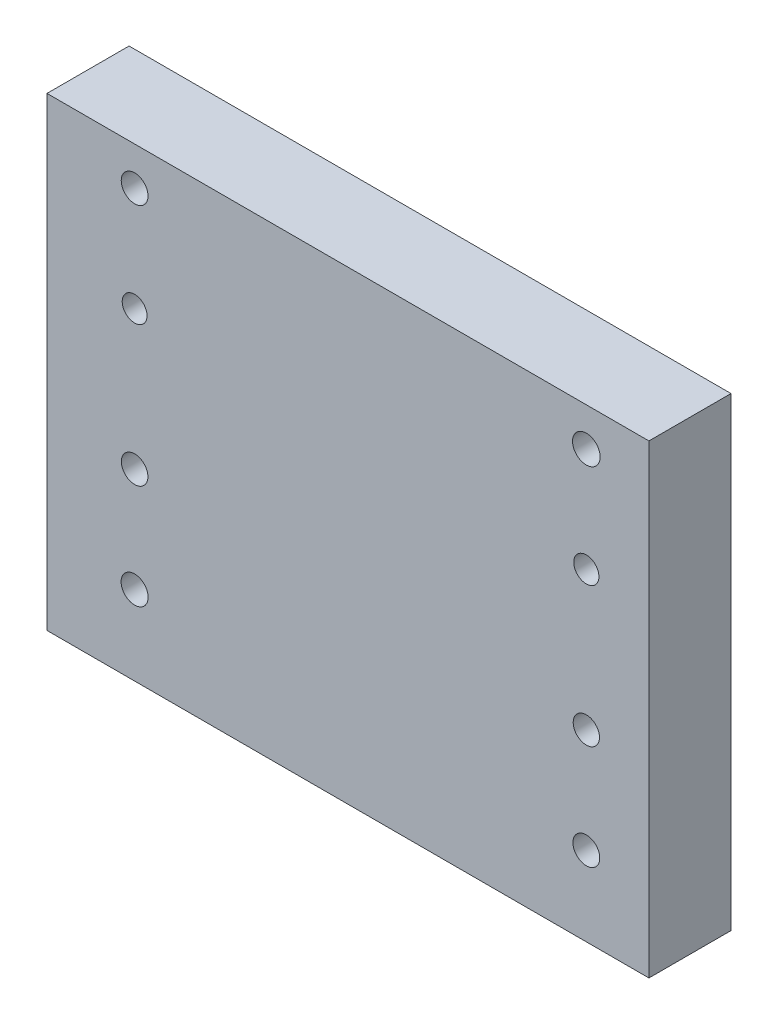
SolidWorks part; units mm, degrees
ref_plane "Plan de face" through (0, 0, 0) normal (0, 0, 1) x (1, 0, 0)
ref_plane "Plan de dessus" through (0, 0, 0) normal (0, 1, 0) x (1, 0, 0)
ref_plane "Plan de droite" through (0, 0, 0) normal (1, 0, 0) x (0, 0, -1)
sketch "Esquisse1" plane through (0, 0, 0) normal (0, 0, 1) x (1, 0, 0)
  line L1 (0, 0) -> (220, 0)
  line L2 (0, 0) -> (0, 170)
  line L3 (0, 170) -> (220, 170)
  line L4 (220, 0) -> (220, 170)
  dimension "D1" = 220
  dimension "D2" = 170
extrude "Boss.-Extru.1" add sketch "Esquisse1" along normal blind 30
sketch "Esquisse2" plane through (0, 0, 0) normal (0, 0, -1) x (-1, 0, 0)
  circle A0 centre (-197.1251, 28.9767) radius 4.9039
  circle A1 centre (-197.1251, 67.0767) radius 4.8016
  circle A2 centre (-197.1251, 117.8767) radius 4.5998
  circle A3 centre (-197.1251, 155.9767) radius 5.0472
  circle A4 centre (-32.0251, 155.9767) radius 4.8967
  circle A5 centre (-32.0251, 117.8767) radius 4.5401
  circle A6 centre (-32.0251, 67.0767) radius 4.8551
  circle A7 centre (-32.0251, 28.9767) radius 4.9397
extrude "Enlèv. mat.-Extru.3" cut sketch "Esquisse2" against normal blind 30
